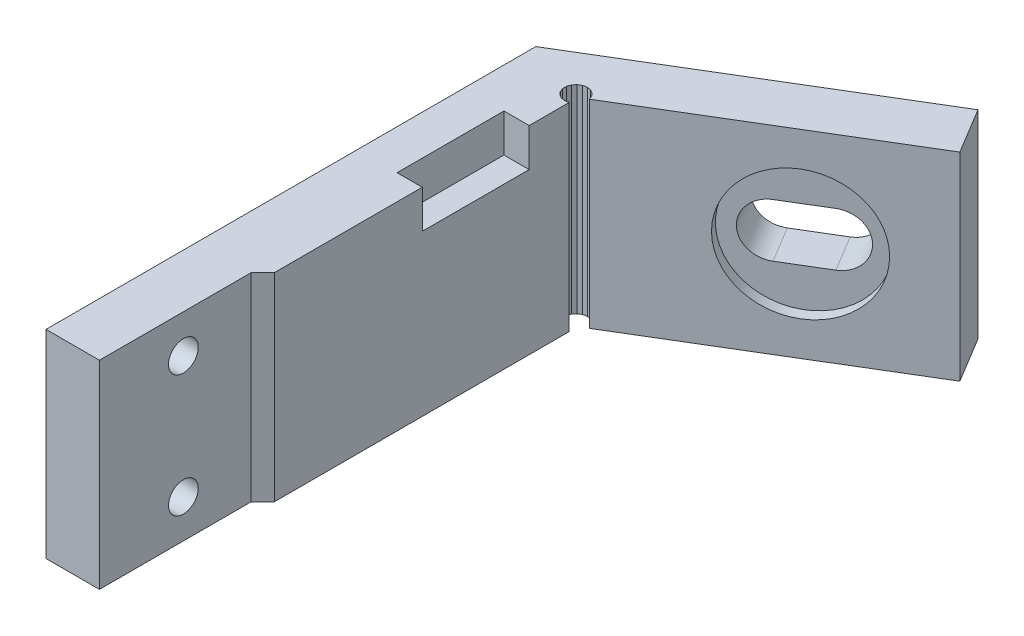
SolidWorks part; units mm, degrees
ref_plane "Front Plane" through (0, 0, 0) normal (0, 0, 1) x (1, 0, 0)
ref_plane "Top Plane" through (0, 0, 0) normal (0, 1, 0) x (1, 0, 0)
ref_plane "Right Plane" through (0, 0, 0) normal (1, 0, 0) x (0, 0, -1)
ref_plane "PY -20.700" through (0, -20.7, 0) normal (0, 1, 0) x (1, 0, 0)
sketch "leg and pad sketch" plane through (0, -20.7, 0) normal (0, 1, 0) x (1, 0, 0)
  line L0 (0.5513, 30.3327) -> (0.3673, 30.8194)
  line L1 (0.3673, 30.8194) -> (0.028, 31.2139)
  line L2 (0.028, 31.2139) -> (-0.4256, 31.4688)
  line L3 (-0.4256, 31.4688) -> (-0.939, 31.5534)
  line L4 (-0.939, 31.5534) -> (-1.4504, 31.4576)
  line L5 (-1.4504, 31.4576) -> (-1.8983, 31.1928)
  line L6 (-1.8983, 31.1928) -> (-2.2288, 30.7909)
  line L7 (-2.2288, 30.7909) -> (-2.4021, 30.3003)
  line L8 (-2.4021, 30.3003) -> (-2.3973, 29.78)
  line L9 (-2.3973, 29.78) -> (-2.2152, 29.2926)
  line L10 (-2.2152, 29.2926) -> (-1.8775, 28.8968)
  line L11 (-1.8775, 28.8968) -> (-1.4248, 28.6402)
  line L12 (-1.4248, 28.6402) -> (-0.9118, 28.5536)
  line L13 (-0.9118, 28.5536) -> (-0.4, 28.6475)
  line L14 (-0.4, 28.6475) -> (-0.4, -9.98)
  line L15 (-0.4, -9.98) -> (-1.92, -11.5)
  line L16 (-1.92, -11.5) -> (-1.92, -31.37)
  line L17 (-1.92, -31.37) -> (-8.92, -31.37)
  line L18 (-8.92, -31.37) -> (-8.92, 32.7926)
  line L19 (-8.92, 32.7926) -> (27.2048, 54.5947)
  line L20 (27.2048, 54.5947) -> (30.8218, 48.6015)
  line L21 (30.8218, 48.6015) -> (0.5513, 30.3327)
extrude "leg and pad" add sketch "leg and pad sketch" along normal mid plane 26
ref_plane "PX -1.350" through (-1.35, 0, 0) normal (1, 0, 0) x (0, 0, -1)
sketch "screw head relief sketch" plane through (-1.35, 0, 0) normal (1, 0, 0) x (0, 0, -1)
  line L0 (23.4, -12.7) -> (23.4, -6.7)
  line L1 (23.4, -6.7) -> (9.4, -6.7)
  line L2 (9.4, -6.7) -> (9.4, -12.7)
  line L3 (9.4, -12.7) -> (23.4, -12.7)
extrude "screw head relief" cut sketch "screw head relief sketch" against normal mid plane 4.7
sketch "insert flange relief sketch" plane through (0, -20.7, 0) normal (0, 1, 0) x (1, 0, 0)
  line L0 (18.3249, 39.8914) -> (17.0331, 42.0318)
  line L1 (17.0331, 42.0318) -> (9.7557, 37.6398)
  line L2 (9.7557, 37.6398) -> (11.0475, 35.4994)
  line L3 (11.0475, 35.4994) -> (18.3249, 39.8914)
revolve "insert flange relief" cut sketch "insert flange relief sketch" angle 360 about L0
sketch "M6 slot end 1 sketch" plane through (0, -20.7, 0) normal (0, 1, 0) x (1, 0, 0)
  line L0 (20.8933, 41.4415) -> (16.243, 49.147)
  line L1 (16.243, 49.147) -> (13.2464, 47.3385)
  line L2 (13.2464, 47.3385) -> (17.8968, 39.633)
  line L3 (17.8968, 39.633) -> (20.8933, 41.4415)
revolve "M6 slot end 1" cut sketch "M6 slot end 1 sketch" angle 360 about L0
sketch "M6 slot end 2 sketch" plane through (0, -20.7, 0) normal (0, 1, 0) x (1, 0, 0)
  line L0 (15.7564, 38.3413) -> (11.106, 46.0467)
  line L1 (11.106, 46.0467) -> (8.1094, 44.2382)
  line L2 (8.1094, 44.2382) -> (12.7598, 36.5328)
  line L3 (12.7598, 36.5328) -> (15.7564, 38.3413)
revolve "M6 slot end 2" cut sketch "M6 slot end 2 sketch" angle 360 about L0
sketch "M6 slot middle sketch" plane through (0, -20.7, 0) normal (0, 1, 0) x (1, 0, 0)
  line L0 (15.7564, 38.3413) -> (20.8933, 41.4415)
  line L1 (20.8933, 41.4415) -> (16.243, 49.147)
  line L2 (16.243, 49.147) -> (11.106, 46.0467)
  line L3 (11.106, 46.0467) -> (15.7564, 38.3413)
extrude "M6 slot middle" cut sketch "M6 slot middle sketch" against normal mid plane 7
ref_plane "PX -5.420" through (-5.42, 0, 0) normal (1, 0, 0) x (0, 0, -1)
sketch "screw holes sketch" plane through (-5.42, 0, 0) normal (1, 0, 0) x (0, 0, -1)
  circle A0 centre (-20.375, -28.7) radius 1.95
  circle A1 centre (-20.375, -12.7) radius 1.95
extrude "screw holes" cut sketch "screw holes sketch" against normal mid plane 9
equation "\"diffL\" = 608.8mm"
equation "\"diffW\" = 329.4mm"
equation "\"diffT\" = 2.9mm"
equation "\"chanSlotW\" = 12.9mm"
equation "\"chanSlotDepth\" = 11.13mm"
equation "\"chanFloor\" = 1.57mm"
equation "\"chanLeg\" = 12.7mm"
equation "\"lightL\" = 605mm"
equation "\"lightW\" = 331mm"
equation "\"lightH\" = 92mm"
equation "\"lightSideFlat\" = 30mm"
equation "\"lightSlopeLen\" = 33.1mm"
equation "\"lightWingDepth\" = 47.9mm"
equation "\"lightWingFlat\" = 90.2mm"
equation "\"lightChanW\" = 99.6mm"
equation "\"lightChanStand\" = 44.1mm"
equation "\"insFlangeD\" = 12.3mm"
equation "\"insFromEnd\" = 20.7mm"
equation "\"insUpSlope\" = 20.8mm"
equation "\"gaugeH\" = 10mm"
equation "\"gaugeStepLen\" = 14mm"
equation "\"gaugeStepW0\" = 13.1mm"
equation "\"gaugeStepDW\" = 0.2mm"
equation "\"gaugeSteps\" = 5mm"
equation "\"gaugeHandleLen\" = 30mm"
equation "\"gaugeHandleW\" = 24mm"
equation "\"gaugeSlot0\" = 3mm"
equation "\"gaugeSlotD\" = 0.1mm"
equation "\"gaugeSlotDepth\" = 8mm"
equation "\"gap\" = 25.4mm"
equation "\"edgeL\" = 1mm"
equation "\"edgeW\" = 0.75mm"
equation "\"proud\" = 1.5mm"
equation "\"seatClr\" = 0.15mm"
equation "\"tongueClrZ\" = 0.1mm"
equation "\"tongueClrX\" = 0.25mm"
equation "\"tongueLen\" = 30mm"
equation "\"armSide\" = 45mm"
equation "\"armEnd\" = 20mm"
equation "\"cornerCham\" = 3mm"
equation "\"brkW\" = 26mm"
equation "\"brkT\" = 7mm"
equation "\"brkSeatClr\" = 0.2mm"
equation "\"brkScrewSpan\" = 16mm"
equation "\"pilotD\" = 2.7mm"
equation "\"pilotDepth\" = 10mm"
equation "\"screwClrD\" = 3.9mm"
equation "\"jogBelow\" = 4mm"
equation "\"padT\" = 7mm"
equation "\"padLen\" = 31mm"
equation "\"m6Clr\" = 7mm"
equation "\"m6Slot\" = 3mm"
equation "\"flangeRelD\" = 17mm"
equation "\"flangeRelDepth\" = 1.5mm"
equation "\"relLen\" = 7mm"
equation "\"relDepth\" = 4mm"
equation "\"relLand\" = 2mm"
equation "\"knockN\" = 100mm"
equation "\"petgcfE\" = 3000mm"
equation "\"mockExtent\" = 110mm"
equation "\"relZnear\" = 9.4mm"
equation "\"relZfar\" = 23.4mm"
equation "\"headD\" = 8mm"
equation "\"headH\" = 2.5mm"
equation "\"headFromEnd\" = 6.8mm"
equation "\"headBack\" = 16.4mm"
equation "\"sideClr\" = 0.4mm"
equation "\"cornerRelR\" = 1.5mm"
equation "\"cornerRelBack\" = 0.6mm"
